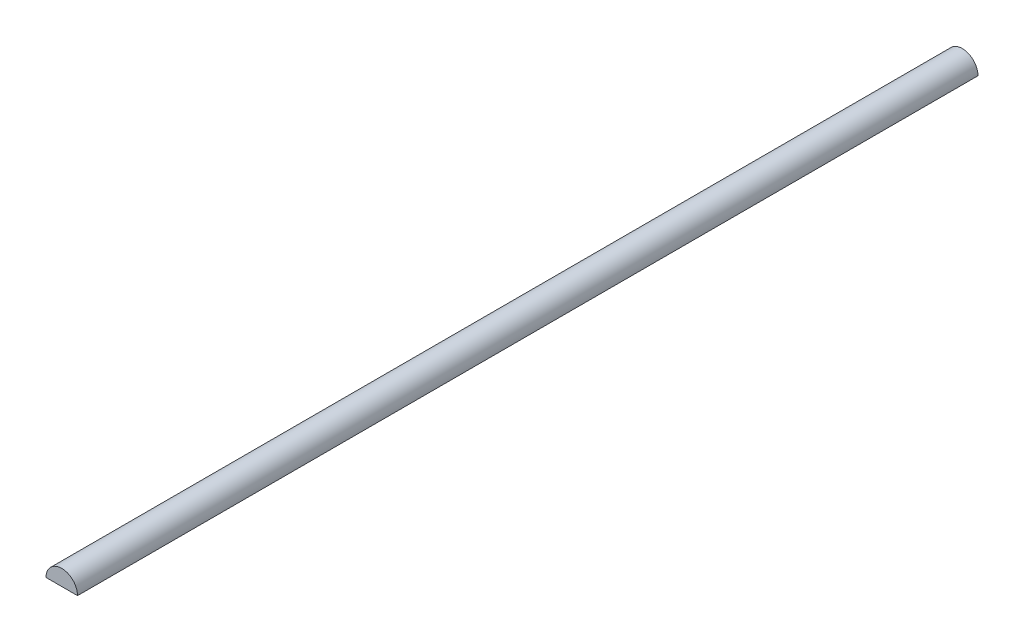
SolidWorks part; units mm, degrees
material "ABS"
ref_plane "Plano frontal" through (0, 0, 0) normal (0, 0, 1) x (1, 0, 0)
ref_plane "Plano superior" through (0, 0, 0) normal (0, 1, 0) x (1, 0, 0)
ref_plane "Plano direito" through (0, 0, 0) normal (1, 0, 0) x (0, 0, -1)
sketch "Esboço1" plane through (0, 0, 0) normal (0, 0, 1) x (1, 0, 0)
  line L1 (-3.5, -5.5651) -> (3.5, -5.5651)
  arc A1 (3.5, -5.5651) -> (-3.5, -5.5651) centre (0, -5.5651) ccw
  dimension "D1" = 3.5
extrude "Ressalto-extrusão1" add sketch "Esboço1" against normal blind 200
